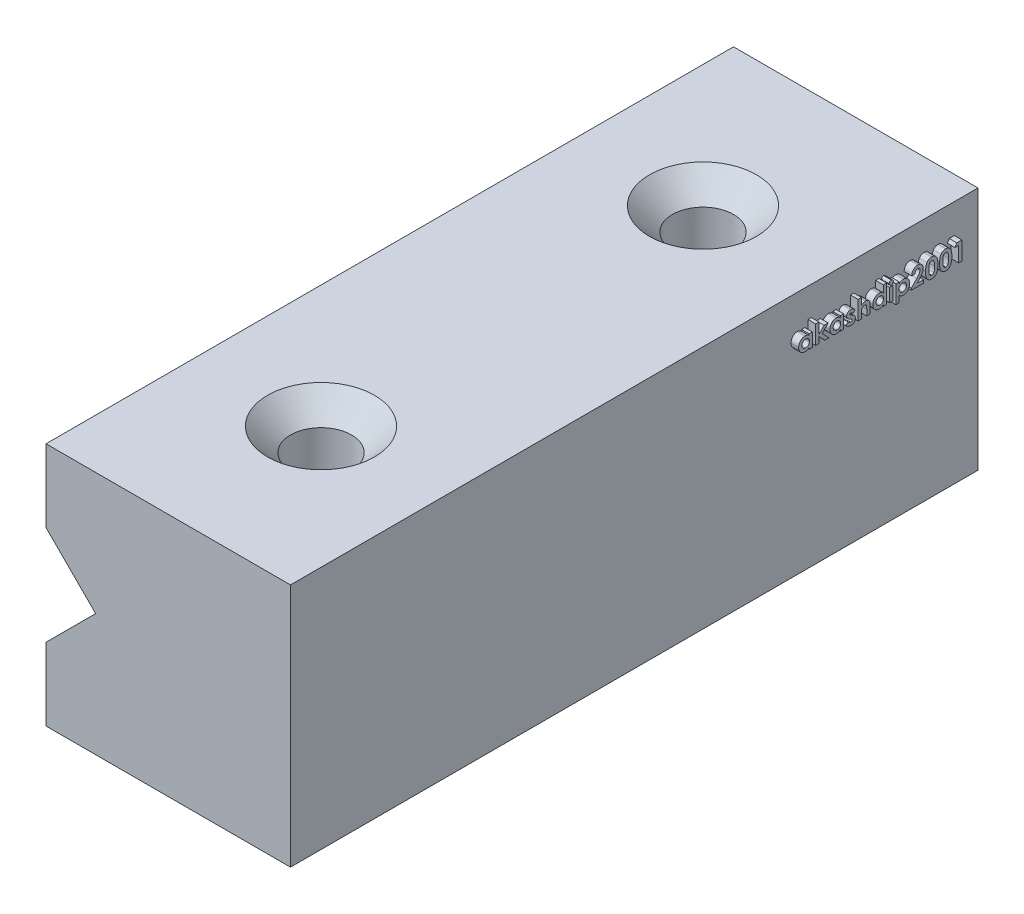
SolidWorks part; units mm, degrees
ref_plane "Front Plane" through (0, 0, 0) normal (0, 0, 1) x (1, 0, 0)
ref_plane "Top Plane" through (0, 0, 0) normal (0, 1, 0) x (1, 0, 0)
ref_plane "Right Plane" through (0, 0, 0) normal (1, 0, 0) x (0, 0, -1)
sketch "Sketch2" plane through (0, 0, 0) normal (0, 0, 1) x (1, 0, 0)
  line L0 (0, 0) -> (0, 50000) construction
  line L1 (0, 0) -> (50000, 0) construction
  line L2 (-16, -6.5) -> (-16, -16)
  line L3 (-16, -16) -> (16, -16)
  line L4 (16, -16) -> (16, 16)
  line L5 (16, 16) -> (-16, 16)
  line L6 (-16, 16) -> (-16, 6.5)
  line L7 (-16, 6.5) -> (-9.5, 0)
  line L8 (-9.5, 0) -> (-16, -6.5)
  point P8 (0, 0)
  point P13 (-11.1352, 0)
  point P14 (-16, 10.3904)
  dimension "D1" = 90
  dimension "D2" = 16
  dimension "D3" = 16
  dimension "D4" = 32
  dimension "D5" = 13
extrude "Boss-Extrude1" add sketch "Sketch2" along normal mid plane 90
hole_wizard "Ø8.0mm Dowel Hole1" positions "Sketch6" profile "Sketch7" hole size "Ø8.0" standard "ISO" end condition through all
sketch "Sketch6" plane through (0, 16, 0) normal (0, 1, 0) x (1, 0, 0)
  point P0 (0, -25)
  point P2 (0, 25)
  point P9 (28.2379, -42.3569)
  point P10 (0, 0)
  point P12 (0, 0)
  dimension "D1" = 50
  dimension "D2" = 25
sketch "Sketch7" plane through (0, 16, 25) normal (1, 0, 0) x (0, 0, 1)
  line L0 (0, 0) -> (0, 32)
  line L1 (0, 32) -> (4, 32)
  line L2 (4, 32) -> (4, 0)
  line L5 (4, 0) -> (0, 0)
  line L11 (0, -6.35) -> (0, 107.95) construction
  dimension "Thru Hole Dia." = 8
  dimension "Thru Hole Depth" = 32
chamfer "Chamfer1" distance 3 angle 45 2 edges at (0, 16, -21) (0, 16, 29)
sketch "Sketch8" plane through (16, 0, 0) normal (1, 0, 0) x (0, 0, -1)
  line L0 (20.3724, 9.7726) -> (42.296, 9.7726) construction
  text T0 "<b>akashdip2001</b>" font "Century Gothic" height in points 9
extrude "Boss-Extrude2" add sketch "Sketch8" along normal mid plane 2
